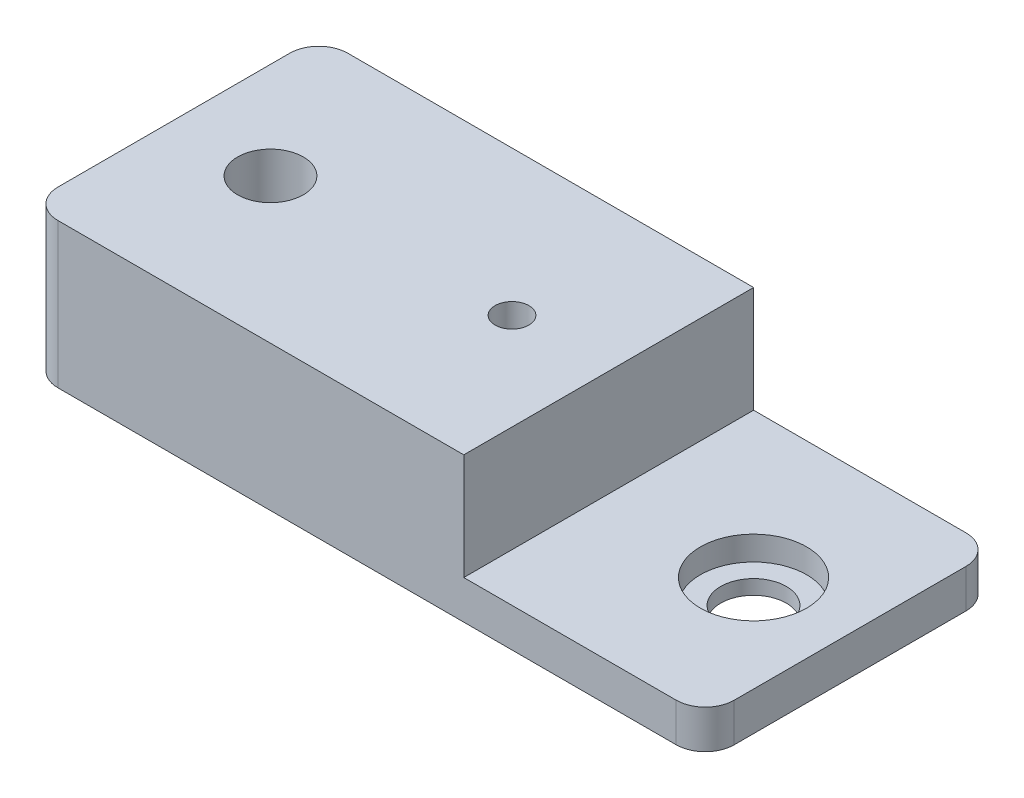
SolidWorks part; units mm, degrees
ref_plane "前视基准面" through (0, 0, 0) normal (0, 0, 1) x (1, 0, 0)
ref_plane "上视基准面" through (0, 0, 0) normal (0, 1, 0) x (1, 0, 0)
ref_plane "右视基准面" through (0, 0, 0) normal (1, 0, 0) x (0, 0, -1)
other "Configuration Table"
sketch "草图1" plane through (0, 0, 0) normal (0, 1, 0) x (1, 0, 0)
  line L1 (-35, -15) -> (35, -15)
  line L2 (-35, -15) -> (-35, 15)
  line L3 (-35, 15) -> (35, 15)
  line L4 (35, -15) -> (35, 15)
  line L5 (-35, -15) -> (35, 15) construction
  line L6 (-35, 15) -> (35, -15) construction
  point P0 (0, 0)
  dimension "D1" = 30
  dimension "D2" = 70
extrude "凸台-拉伸1" add sketch "草图1" along normal blind 15
fillet "圆角1" radius 3 4 edges at (35, 7.5, -15) (35, 7.5, 15) (-35, 7.5, 15) (-35, 7.5, -15)
sketch "草图5" plane through (0, 15, 0) normal (0, 1, 0) x (1, 0, 0)
  circle A0 centre (0, 0) radius 1.75
  circle A1 centre (-25, 0) radius 3.4
  circle A2 centre (25, 0) radius 3.4
  dimension "D1" = 3.5
  dimension "D2" = 6.8
  dimension "D3" = 6.8
  dimension "D4" = 25
  dimension "D5" = 25
extrude "切除-拉伸1" cut sketch "草图5" against normal through all
sketch "草图6" plane through (0, 0, 0) normal (0, -1, 0) x (1, 0, 0)
  line L1 (0, 3.5796) -> (-3.1, 1.7898)
  line L2 (-3.1, 1.7898) -> (-3.1, -1.7898)
  line L3 (-3.1, -1.7898) -> (0, -3.5796)
  line L4 (0, -3.5796) -> (3.1, -1.7898)
  line L5 (3.1, -1.7898) -> (3.1, 1.7898)
  line L6 (3.1, 1.7898) -> (0, 3.5796)
  circle A0 centre (0, 0) radius 3.1 construction
  dimension "D1" = 6.2
extrude "切除-拉伸2" cut sketch "草图6" against normal blind 7.8
sketch "草图7" plane through (0, 15, 0) normal (0, 1, 0) x (1, 0, 0)
  line L1 (10.0087, 16.8498) -> (40.0896, 16.8498)
  line L2 (10.0087, 16.8498) -> (10.0087, -19.0847)
  line L3 (10.0087, -19.0847) -> (40.0896, -19.0847)
  line L4 (40.0896, 16.8498) -> (40.0896, -19.0847)
extrude "切除-拉伸4" cut sketch "草图7" against normal blind 11 contours L4 L3 L2 L1
sketch "草图9" plane through (0, 4, 0) normal (0, 1, 0) x (1, 0, 0)
  circle A0 centre (25, 0) radius 5.5
  dimension "D1" = 11
extrude "切除-拉伸5" cut sketch "草图9" against normal blind 2.5
